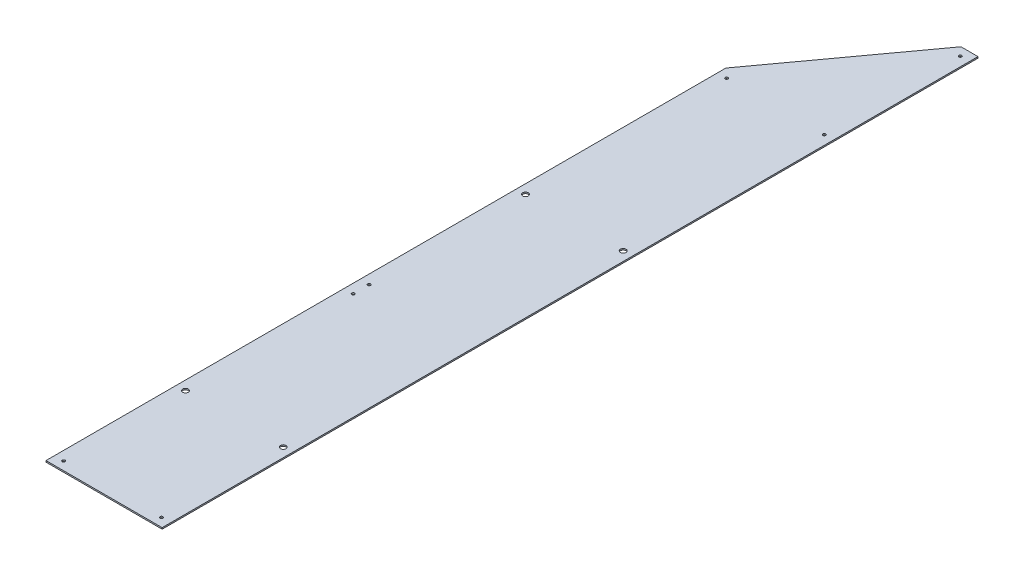
SolidWorks part; units mm, degrees
material "Balsa"
ref_plane "Front Plane" through (0, 0, 0) normal (0, 0, 1) x (1, 0, 0)
ref_plane "Top Plane" through (0, 0, 0) normal (0, 1, 0) x (1, 0, 0)
ref_plane "Right Plane" through (0, 0, 0) normal (1, 0, 0) x (0, 0, -1)
sketch "Sketch1" plane through (0, 0, 0) normal (0, 1, 0) x (1, 0, 0)
  line L1 (-65.0875, -457.2) -> (65.0875, -457.2)
  line L2 (-65.0875, -457.2) -> (-65.0875, 457.2)
  line L3 (-65.0875, 457.2) -> (65.0875, 457.2)
  line L4 (65.0875, -457.2) -> (65.0875, 457.2)
  line L5 (-65.0875, -457.2) -> (65.0875, 457.2) construction
  line L6 (-65.0875, 457.2) -> (65.0875, -457.2) construction
  point P0 (0, 0)
  dimension "D1" = 914.4
  dimension "D2" = 130.175
extrude "Boss-Extrude1" add sketch "Sketch1" against normal blind 1.5875
sketch "Sketch2" plane through (0, 0, 0) normal (0, 1, 0) x (1, 0, 0)
  line L0 (54.7687, -457.2) -> (54.7687, 457.2) construction
  line L1 (-65.0875, -457.2) -> (65.0875, -457.2) construction
  line L2 (65.0875, 457.2) -> (-65.0875, 457.2) construction
  line L3 (65.0875, -457.2) -> (65.0875, 457.2) construction
  line L4 (54.7687, 295.275) -> (54.7687, 447.675) construction
  circle A0 centre (54.7687, -447.675) radius 1.5875
  circle A1 centre (54.7687, -311.15) radius 3.175
  circle A2 centre (54.7687, 447.675) radius 1.5875
  circle A3 centre (54.7687, 69.85) radius 3.175
  circle A4 centre (54.7687, 295.275) radius 1.5875
  dimension "D4" = 3.175
  dimension "D5" = 6.35
  dimension "D8" = 3.175
  dimension "D9" = 6.35
  dimension "D10" = 152.4
  dimension "D1" = 10.3187
  dimension "D2" = 9.525
  dimension "D3" = 136.525
  dimension "D6" = 9.525
  dimension "D7" = 381
extrude "Cut-Extrude2" cut sketch "Sketch2" against normal through all
ref_plane "Plane1" through (0, 0, 0) normal (-1, 0, 0) x (0, 0, 1)
mirror "Mirror2" about plane through (0, 0, 0) normal (-1, 0, 0) of "Cut-Extrude2"
sketch "Sketch3" plane through (0, -1.5875, 0) normal (0, -1, 0) x (1, 0, 0)
  line L0 (46.0375, -457.2) -> (-65.0875, -457.2)
  line L2 (65.0875, -457.2) -> (-65.0875, -457.2) construction
  line L3 (54.7687, -447.675) -> (54.7687, -457.2) construction
  line L5 (54.7687, -457.2) -> (46.0375, -457.2) construction
  line L6 (-54.7687, -295.275) -> (-65.0875, -295.275) construction
  line L8 (54.7687, -447.675) -> (65.0875, -447.675) construction
  line L9 (65.0875, 457.2) -> (65.0875, -457.2) construction
  line L10 (54.7687, 447.675) -> (65.0875, 447.675)
  line L11 (-65.0875, -295.275) -> (-65.0875, -304.8) construction
  line L12 (-65.0875, -457.2) -> (-65.0875, 457.2) construction
  line L13 (-65.0875, -304.8) -> (46.0375, -457.2)
  line L14 (-65.0875, -304.8) -> (-65.0875, -457.2)
  circle M7 centre (-54.7687, -447.675) radius 1.5875
  line M16 (-65.0875, 457.2) -> (-65.0875, -457.2)
  line M17 (-65.0875, -457.2) -> (65.0875, -457.2)
  dimension "D2" = 8.7313
  dimension "D3" = 10.3188
  dimension "D4" = 9.525
extrude "Cut-Extrude3" cut sketch "Sketch3" against normal through all contours L13 M16 M17 M7
sketch "Sketch5" plane through (0, -1.5875, 0) normal (0, -1, 0) x (-1, 0, 0)
  line L0 (54.7687, -114.3) -> (54.7687, -118.11) construction
  line L1 (65.0875, -457.2) -> (-65.0875, -457.2) construction
  line L3 (54.7687, -447.675) -> (54.7687, -114.3) construction
  line L4 (54.7687, -114.3) -> (8.7573, -114.3) construction
  circle A0 centre (54.7687, -123.19) radius 1.5875
  circle A2 centre (54.7687, -105.41) radius 1.5875
  dimension "D1" = 8.89
  dimension "D2" = 342.9
extrude "StrutMountingHoles" cut sketch "Sketch5" against normal through all both and the other way through all
